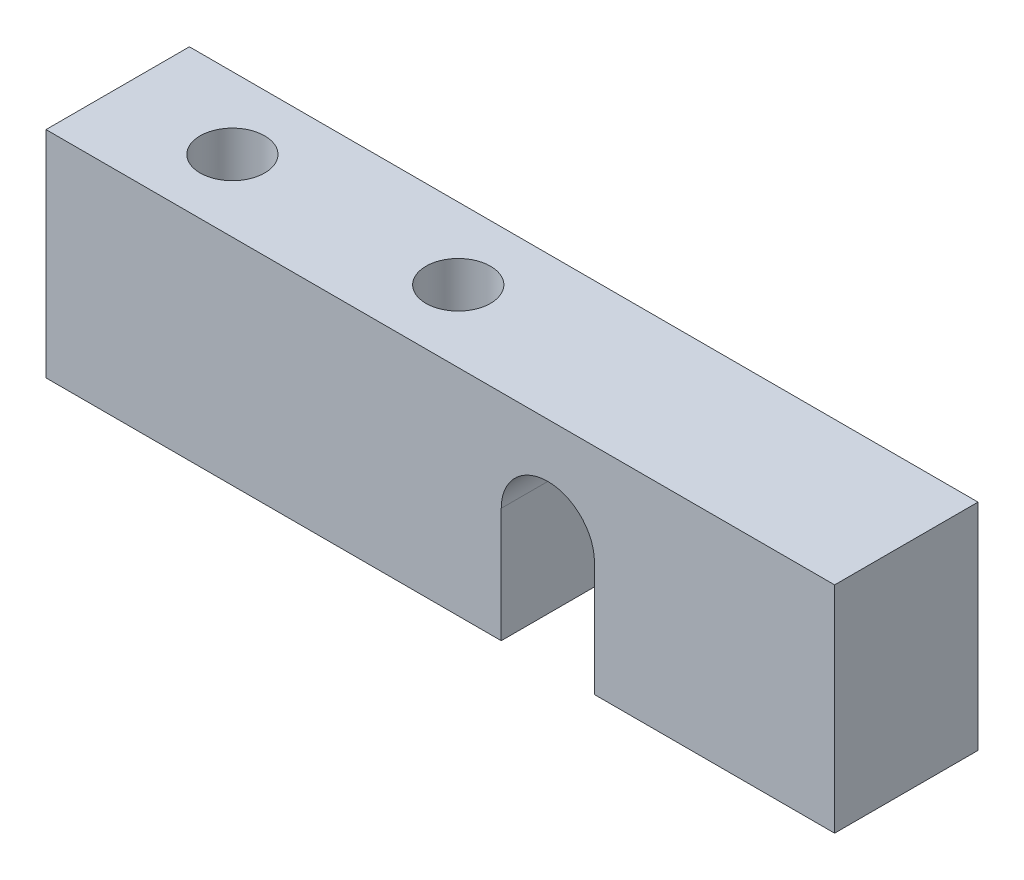
SolidWorks part; units mm, degrees
material "3.3547 (EN-AW 5083)"
ref_plane "Ebene vorne" through (0, 0, 0) normal (0, 0, 1) x (1, 0, 0)
ref_plane "Ebene oben" through (0, 0, 0) normal (0, 1, 0) x (1, 0, 0)
ref_plane "Ebene rechts" through (0, 0, 0) normal (1, 0, 0) x (0, 0, -1)
sketch "Skizze1" plane through (0, 0, 0) normal (0, 1, 0) x (1, 0, 0)
  line L1 (-38.5475, -6.6013) -> (16.4525, -6.6013)
  line L2 (-38.5475, -6.6013) -> (-38.5475, -16.6013)
  line L3 (-38.5475, -16.6013) -> (16.4525, -16.6013)
  line L4 (16.4525, -6.6013) -> (16.4525, -16.6013)
  dimension "D1" = 10
  dimension "D2" = 55
extrude "Aufsatz-Linear austragen1" add sketch "Skizze1" along normal blind 15
sketch "Skizze2" plane through (0, 0, 6.6013) normal (0, 0, -1) x (-1, 0, 0)
  line L5 (-16.4525, 15) -> (38.5475, 15) construction
  line L6 (-16.4525, 15) -> (-16.4525, 0) construction
  line L7 (0.2975, 8) -> (0.2975, 0)
  line L8 (-16.4525, 0) -> (38.5475, 0) construction
  line L9 (0.2975, 0) -> (6.7975, 0)
  line L10 (6.7975, 0) -> (6.7975, 8)
  arc A1 (6.7975, 8) -> (0.2975, 8) centre (3.5475, 8) ccw
  dimension "D1" = 7
  dimension "D2" = 20
extrude "Schnitt-Linear austragen1" cut sketch "Skizze2" against normal blind 15
sketch "Skizze3" plane through (0, 0, 0) normal (0, -1, 0) x (1, 0, 0)
  line L0 (-38.5475, 6.6013) -> (-38.5475, 16.6013) construction
  line L1 (-6.7975, 6.6013) -> (-6.7975, 16.6013) construction
  circle A0 centre (-14.7975, 11.6013) radius 1
  circle A1 centre (-30.5475, 11.6013) radius 1
  dimension "D1" = 8
  dimension "D2" = 8
extrude "Schnitt-Linear austragen2" cut sketch "Skizze3" against normal blind 20
hole_wizard "Formsenkung für M4 Senkschraube mit Innensechskant1" positions "3D-Skizze1" profile "Skizze4" countersink size "M4" standard "DIN"
sketch3d "3D-Skizze1"
  line L0 (-30.5475, 15, 11.6013) -> (-30.5475, 0, 11.6013) construction
  line L1 (-14.7975, 15, 11.6013) -> (-14.7975, 0, 11.6013) construction
  point P0 (-30.5475, 0, 11.6013)
  point P4 (-14.7975, 0, 11.6013)
sketch "Skizze4" plane through (-30.5475, 0, 11.6013) normal (1, 0, 0) x (0, 0, -1)
  line L0 (0, 0) -> (0, 22.8519)
  line L1 (0, 22.8519) -> (2.25, 21.5)
  line L2 (2.25, 21.5) -> (2.25, 2.34)
  line L3 (2.25, 2.34) -> (4.59, 0)
  line L5 (4.59, 0) -> (0, 0)
  line L6 (-2.25, 2.34) -> (-4.59, 0) construction
  line L10 (0, 22.8519) -> (-2.25, 21.5) construction
  line L11 (0, -6.35) -> (0, 107.95) construction
  dimension "Bohrerdurchmesser" = 4.5
  dimension "Bohrungstiefe" = 21.5
  dimension "Senkdurchmesser (Oben)" = 9.18
  dimension "Senkwinkel (Oben)" = 90
  dimension "Spitzenwinkel" = 118
